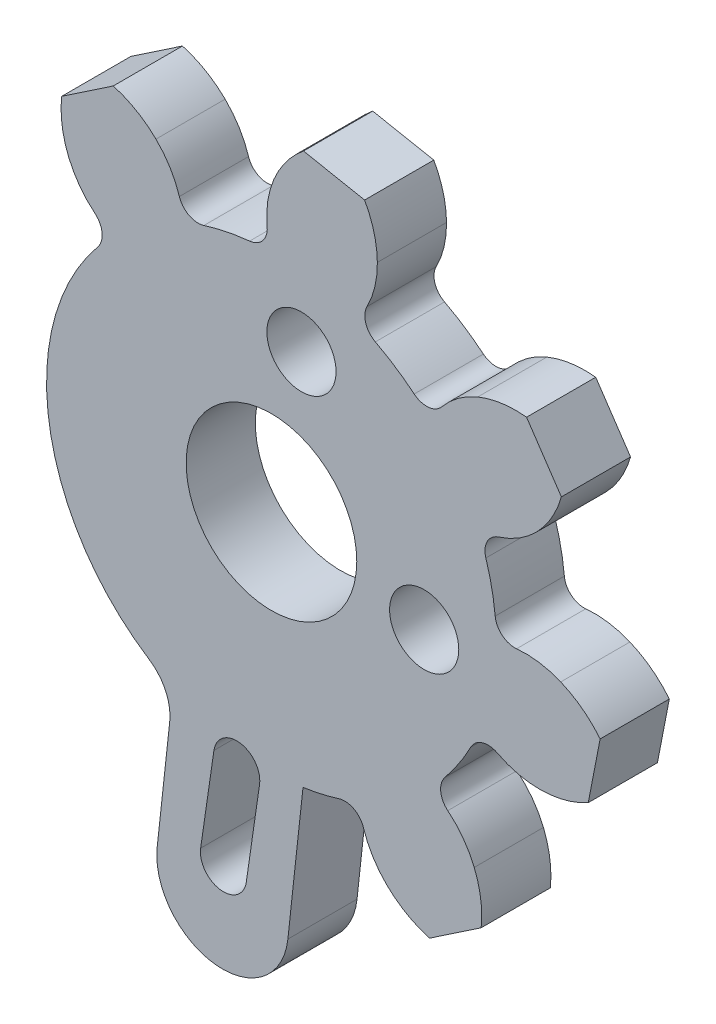
SolidWorks part; units mm, degrees
ref_plane "Front Plane" through (0, 0, 0) normal (0, 0, 1) x (1, 0, 0)
ref_plane "Top Plane" through (0, 0, 0) normal (0, 1, 0) x (1, 0, 0)
ref_plane "Right Plane" through (0, 0, 0) normal (1, 0, 0) x (0, 0, -1)
sketch "Sketch1" plane through (0, 0, 0) normal (0, 0, 1) x (1, 0, 0)
  line L0 (13.7405, -4.0425) -> (14.2553, -1.392)
  line L5 (12.5744, 6.8575) -> (11.0643, 9.0957)
  line L6 (4.0425, 13.7405) -> (1.392, 14.2553)
  line L7 (-6.8575, 12.5744) -> (-9.0957, 11.0643)
  line L8 (0.0022, -0.0003) -> (6.6251, -1.1019) construction
  line L9 (1.3031, 6.669) -> (0.0022, -0.0003) construction
  line L10 (0.0022, -0.0003) -> (7.5307, -6.1928) construction
  line L11 (0.0022, -0.0003) -> (2.926, -9.3006) construction
  line L15 (1.3705, -9.6532) -> (0.0022, -0.0003) construction
  line L16 (0.0022, -0.0003) -> (-5.3081, -8.1784) construction
  line L17 (-10.7399, 0) -> (13.4798, 0) construction
  line L19 (-4.409, -10.0722) -> (-4.9524, -15.0642)
  line L20 (0.7143, -15.6795) -> (1.3705, -9.6532)
  line L21 (6.8575, -12.5744) -> (9.0957, -11.0643)
  line L24 (-2.0789, -14.2997) -> (-1.5028, -10.3414) construction
  line L25 (-3.0685, -14.1556) -> (-2.4924, -10.1973)
  line L26 (-1.0894, -14.4437) -> (-0.5133, -10.4854)
  line L27 (-2.0789, -14.2997) -> (0.0022, -0.0003) construction
  arc A0 (-7.5307, 6.1928) -> (-5.3081, -8.1784) centre (0, 0) ccw
  arc A1 (11.6741, -4.5947) -> (13.7405, -4.0425) centre (11.6161, -0.2354) ccw
  arc A2 (9.7911, -4.1469) -> (11.6741, -4.5947) centre (11.6214, -0.6327) ccw
  arc A3 (14.2553, -1.392) -> (12.546, -0.1064) centre (10.8602, -4.1268) ccw
  arc A4 (12.546, -0.1064) -> (10.6323, 0.1835) centre (11.0138, -3.7604) ccw
  arc A5 (9.704, 0.946) -> (10.6323, 0.1835) centre (10.5494, 1.0289) ccw
  arc A6 (9.7911, -4.1469) -> (8.6455, -4.5075) centre (9.3987, -4.9003) ccw
  arc A7 (11.5038, 5.0059) -> (12.5744, 6.8575) centre (8.3803, 8.0473) ccw
  arc A8 (9.8557, 3.991) -> (11.5038, 5.0059) centre (8.665, 7.7702) ccw
  arc A9 (11.0643, 9.0957) -> (8.9466, 8.7962) centre (10.5974, 4.7612) ccw
  arc A10 (8.9466, 8.7962) -> (7.3884, 7.6479) centre (10.447, 5.1289) ccw
  arc A11 (6.1928, 7.5307) -> (7.3884, 7.6479) centre (6.732, 8.1871) ccw
  arc A12 (9.8557, 3.991) -> (9.3006, 2.926) centre (10.1109, 3.1808) ccw
  arc A13 (4.5947, 11.6741) -> (4.0425, 13.7405) centre (0.2354, 11.6161) ccw
  arc A14 (4.1469, 9.7911) -> (4.5947, 11.6741) centre (0.6327, 11.6214) ccw
  arc A15 (1.392, 14.2553) -> (0.1064, 12.546) centre (4.1268, 10.8602) ccw
  arc A16 (0.1064, 12.546) -> (-0.1835, 10.6323) centre (3.7604, 11.0138) ccw
  arc A17 (-0.946, 9.704) -> (-0.1835, 10.6323) centre (-1.0289, 10.5494) ccw
  arc A18 (4.1469, 9.7911) -> (4.5075, 8.6455) centre (4.9003, 9.3987) ccw
  arc A19 (-5.0059, 11.5038) -> (-6.8575, 12.5744) centre (-8.0473, 8.3803) ccw
  arc A20 (-3.991, 9.8557) -> (-5.0059, 11.5038) centre (-7.7702, 8.665) ccw
  arc A21 (-9.0957, 11.0643) -> (-8.7962, 8.9466) centre (-4.7612, 10.5974) ccw
  arc A22 (-8.7962, 8.9466) -> (-7.6479, 7.3884) centre (-5.1289, 10.447) ccw
  arc A23 (-7.5307, 6.1928) -> (-7.6479, 7.3884) centre (-8.1871, 6.732) ccw
  arc A24 (-3.991, 9.8557) -> (-2.926, 9.3006) centre (-3.1808, 10.1109) ccw
  arc A25 (-0.946, 9.704) -> (-2.926, 9.3006) centre (0, 0) ccw
  arc A26 (6.1928, 7.5307) -> (4.5075, 8.6455) centre (0, 0) ccw
  arc A27 (9.704, 0.946) -> (9.3006, 2.926) centre (0, 0) ccw
  arc A28 (7.5307, -6.1928) -> (8.6455, -4.5075) centre (0, 0) ccw
  arc A29 (1.3705, -9.6532) -> (2.926, -9.3006) centre (0, 0) ccw
  circle A32 centre (-1.5028, -10.3414) radius 0.6
  circle A33 centre (-2.0789, -14.2997) radius 0.6
  arc A36 (-3.0685, -14.1556) -> (-1.0894, -14.4437) centre (-2.0789, -14.2997) ccw
  circle A37 centre (6.6251, -1.1019) radius 1.5
  circle A38 centre (0.0022, -0.0003) radius 3.7
  circle A39 centre (1.3031, 6.669) radius 1.5
  arc A40 (-0.5133, -10.4854) -> (-2.4924, -10.1973) centre (-1.5028, -10.3414) ccw
  arc A87 (-4.409, -10.0722) -> (-5.3081, -8.1784) centre (-6.3973, -9.8558) ccw
  arc A88 (-4.9524, -15.0642) -> (0.7143, -15.6795) centre (-2.1191, -15.3726) ccw
  arc A90 (3.991, -9.8557) -> (2.926, -9.3006) centre (3.1808, -10.1109) ccw
  arc A91 (3.991, -9.8557) -> (5.0059, -11.5038) centre (7.7702, -8.665) ccw
  arc A92 (5.0059, -11.5038) -> (6.8575, -12.5744) centre (8.0473, -8.3803) ccw
  arc A93 (9.0957, -11.0643) -> (8.7962, -8.9466) centre (4.7612, -10.5974) ccw
  arc A94 (8.7962, -8.9466) -> (7.6479, -7.3884) centre (5.1289, -10.447) ccw
  arc A95 (7.5307, -6.1928) -> (7.6479, -7.3884) centre (8.1871, -6.732) ccw
  point P82 (0, 0)
  point P86 (-1.7909, -12.3205)
  point P94 (-1.5351, -10.2547)
  dimension "D1" = 19.5
  dimension "D2" = 0.8495
  dimension "D3" = 3.9623
  dimension "D4" = 4.3596
  dimension "D6" = 4.3596
  dimension "D7" = 3.9623
  dimension "D8" = 0.8495
  dimension "D9" = 2
  dimension "D11" = 2.85
  dimension "D15" = 1
  dimension "D18" = 3
  dimension "D19" = 3
  dimension "D20" = 7.4
  dimension "D26" = 16.349
  dimension "D5" = 2.7
  dimension "D10" = 5.0215
  dimension "D12" = 6.0619
  dimension "D14" = 4
  dimension "D16" = 6.795
  dimension "D17" = 6.7138
  dimension "D21" = 57.003
  dimension "D22" = 41.065
  dimension "D23" = 9.444
  dimension "D24" = 29.995
  dimension "D25" = 33.109
  dimension "D27" = 10.45
  dimension "D13" = 5
extrude "Boss-Extrude1" add sketch "Sketch1" along normal blind 3 contours A95 A28 A6 A2 A1 L0 A3 A4 A5 A27 A12 A8 A7 L5 A9 A10 A11 A26 A18 A14 A13 L6 A15 A16 A17 A25 A24 A20 A19 L7 A21 A22 A23 A0 A87 L19 A88 L20 A29 A90 A91 A92 L21 A93 A94 A40 L26 A36 L25
